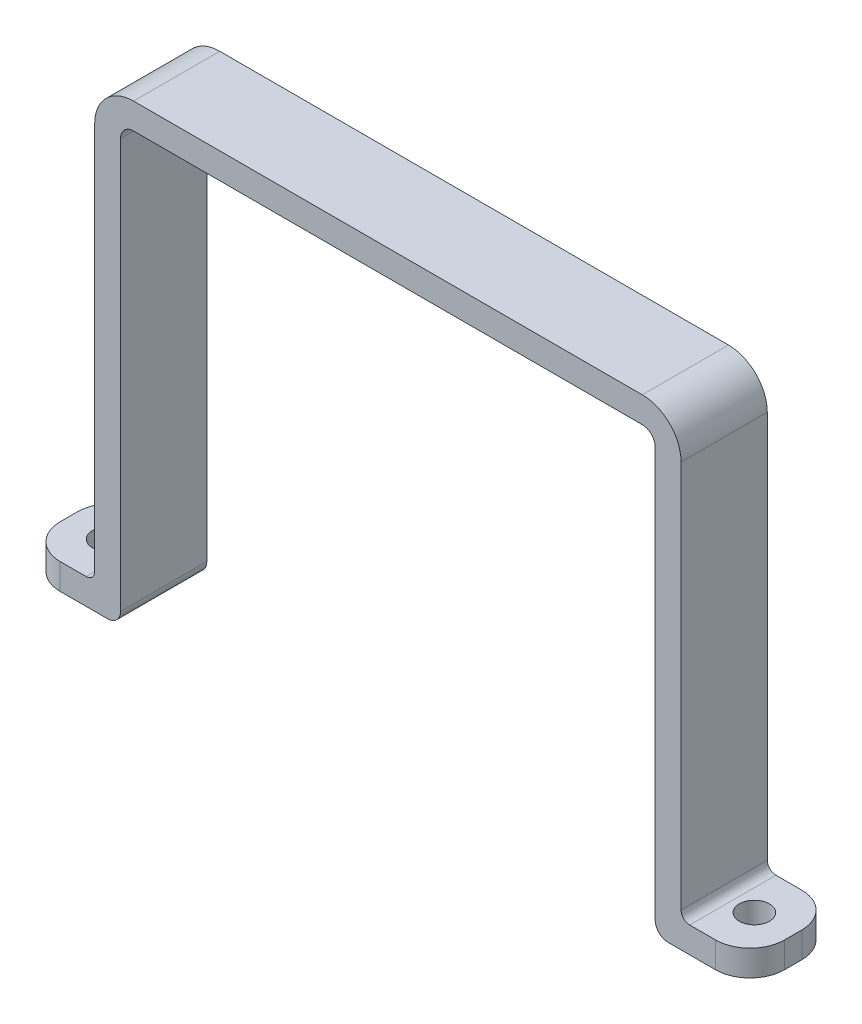
SolidWorks part; units mm, degrees
material "Acrílico (Impacto medio-alto)"
ref_plane "Alzado" through (0, 0, 0) normal (0, 0, 1) x (1, 0, 0)
ref_plane "Planta" through (0, 0, 0) normal (0, 1, 0) x (1, 0, 0)
ref_plane "Vista lateral" through (0, 0, 0) normal (1, 0, 0) x (0, 0, -1)
sketch "Croquis1" plane through (0, 0, 0) normal (0, 0, 1) x (1, 0, 0)
  line L0 (0, 0) -> (11, 0)
  line L1 (11, 0) -> (11, 50.5)
  line L2 (11, 50.5) -> (73, 50.5)
  line L3 (73, 50.5) -> (73, 0)
  line L4 (73, 0) -> (84, 0)
  line L5 (84, 0) -> (84, 3)
  line L6 (84, 3) -> (76, 3)
  line L7 (76, 3) -> (76, 53.5)
  line L8 (76, 53.5) -> (8, 53.5)
  line L9 (8, 53.5) -> (8, 3)
  line L10 (8, 3) -> (0, 3)
  line L11 (0, 3) -> (0, 0)
  dimension "D1" = 3
  dimension "D2" = 3
  dimension "D3" = 3
  dimension "D4" = 3
  dimension "D5" = 3
  dimension "D6" = 62
  dimension "D7" = 50.5
  dimension "D8" = 11
extrude "Saliente-Extruir1" add sketch "Croquis1" along normal mid plane 10
ref_plane "Plano1" through (42, 0, 0) normal (1, 0, 0) x (0, 0, -1)
fillet "Redondeo1" radius 4 4 edges at (0, 1.5, -5) (0, 1.5, 5) (84, 1.5, -5) (84, 1.5, 5)
sketch "Croquis2" plane through (0, 3, 0) normal (0, 1, 0) x (1, 0, 0)
  line L1 (84, -1) -> (84, 1) construction
  line L2 (80, -5) -> (76, -5) construction
  circle A0 centre (79.5, 0) radius 1.75
  dimension "D1" = 3.5
  dimension "D2" = 4.5
  dimension "D3" = 5
extrude "Cortar-Extruir1" cut sketch "Croquis2" against normal through all
mirror "Simetría1" about plane through (42, 0, 0) normal (1, 0, 0) of "Cortar-Extruir1"
fillet "Redondeo2" radius 1.5 2 edges at (11, 50.5, 0) (73, 50.5, 0)
fillet "Redondeo3" radius 4.5 2 edges at (76, 53.5, 0) (8, 53.5, 0)
fillet "Redondeo4" radius 1.5 2 edges at (73, 0, 0) (11, 0, 0)
fillet "Redondeo5" radius 1 2 edges at (76, 3, 0) (8, 3, 0)
